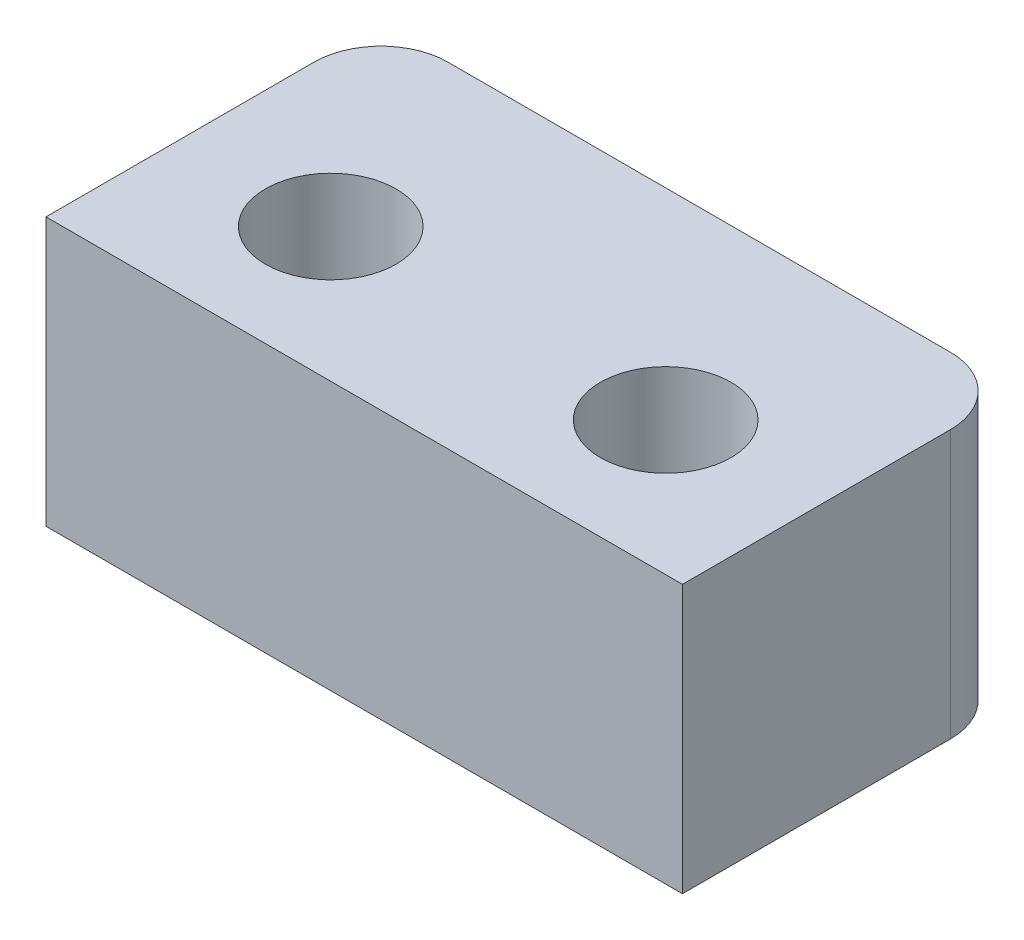
SolidWorks part; units mm, degrees
ref_plane "Спереди" through (0, 0, 0) normal (0, 0, 1) x (1, 0, 0)
ref_plane "Сверху" through (0, 0, 0) normal (0, 1, 0) x (1, 0, 0)
ref_plane "Справа" through (0, 0, 0) normal (1, 0, 0) x (0, 0, -1)
sketch "Эскиз1" plane through (0, 0, 0) normal (0, 1, 0) x (1, 0, 0)
  line L1 (15, -7.5) -> (-15, -7.5)
  line L2 (15, -7.5) -> (15, 7.5)
  line L3 (15, 7.5) -> (-15, 7.5)
  line L4 (-15, -7.5) -> (-15, 7.5)
  line L5 (15, -7.5) -> (-15, 7.5) construction
  line L6 (15, 7.5) -> (-15, -7.5) construction
  point P0 (0, 0)
  dimension "D1" = 30
  dimension "D2" = 15
extrude "Бобышка-Вытянуть1" add sketch "Эскиз1" along normal blind 8
fillet "Скругление1" radius 6 2 edges at (-15, 4, -7.5) (15, 4, -7.5)
sketch "Эскиз2" plane through (0, 8, 0) normal (0, 1, 0) x (1, 0, 0)
  line L0 (0, 9.5664) -> (0, -9.7823) construction
  line L1 (-15, -7.5) -> (15, -7.5) construction
  circle A0 centre (-5, -3.5) radius 1.95
  circle A1 centre (5, -3.5) radius 1.95
  dimension "D1" = 3.9
  dimension "D2" = 10
  dimension "D3" = 4
extrude "Вырез-Вытянуть1" cut sketch "Эскиз2" against normal through all
sketch "Эскиз3" plane through (0, 8, 0) normal (0, 1, 0) x (1, 0, 0)
  line L1 (9.5, -7.5) -> (-9.5, -7.5)
  line L2 (9.5, -7.5) -> (9.5, 2.5)
  line L3 (9.5, 2.5) -> (-9.5, 2.5)
  line L4 (-9.5, -7.5) -> (-9.5, 2.5)
  line L5 (9.5, -7.5) -> (-9.5, 2.5) construction
  line L6 (9.5, 2.5) -> (-9.5, -7.5) construction
  line L7 (0, 12.8806) -> (0, -9.8077) construction
  line L8 (-15, -7.5) -> (15, -7.5) construction
  point P0 (0, 0)
  dimension "D1" = 19
  dimension "D2" = 10
extrude "Вырез-Вытянуть3" cut sketch "Эскиз3" against normal blind 10 flip side to cut
fillet "Скругление3" radius 2 2 edges at (9.5, 4, -2.5) (-9.5, 4, -2.5)
